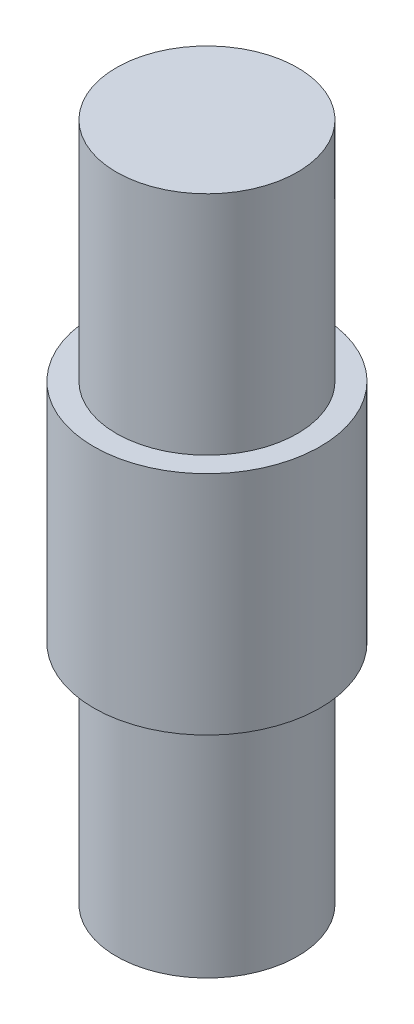
SolidWorks part; units mm, degrees
ref_plane "前视基准面" through (0, 0, 0) normal (0, 0, 1) x (1, 0, 0)
ref_plane "上视基准面" through (0, 0, 0) normal (0, 1, 0) x (1, 0, 0)
ref_plane "右视基准面" through (0, 0, 0) normal (1, 0, 0) x (0, 0, -1)
other "Configuration Table"
sketch "草图1" plane through (0, 0, 0) normal (0, 1, 0) x (1, 0, 0)
  circle A0 centre (0, 0) radius 5
  dimension "D1" = 10
extrude "凸台-拉伸4" add sketch "草图1" along normal blind 10
sketch "草图4" plane through (0, 10, 0) normal (0, 1, 0) x (1, 0, 0)
  circle A0 centre (0, 0) radius 4
  dimension "D1" = 8
extrude "凸台-拉伸5" add sketch "草图4" along normal blind 10
sketch "草图5" plane through (0, 0, 0) normal (0, -1, 0) x (1, 0, 0)
  circle A0 centre (0, 0) radius 4
  dimension "D1" = 8
extrude "凸台-拉伸6" add sketch "草图5" along normal blind 10
